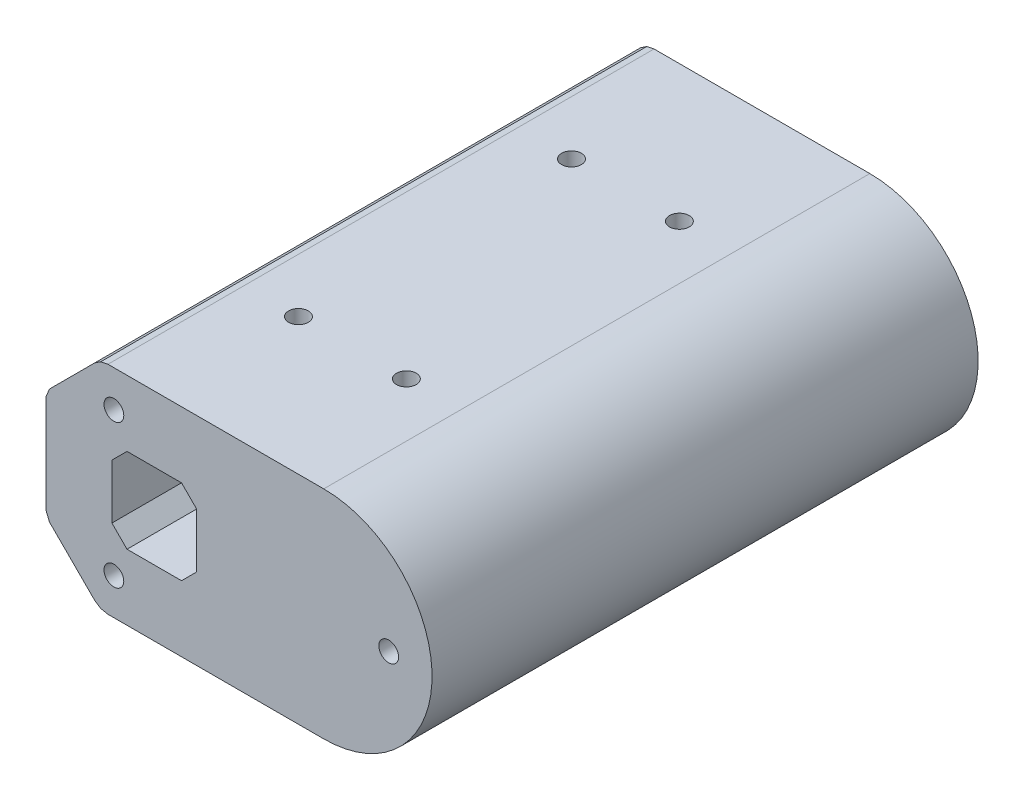
SolidWorks part; units mm, degrees
ref_plane "前视基准面" through (0, 0, 0) normal (0, 0, 1) x (1, 0, 0)
ref_plane "上视基准面" through (0, 0, 0) normal (0, 1, 0) x (1, 0, 0)
ref_plane "右视基准面" through (0, 0, 0) normal (1, 0, 0) x (0, 0, -1)
sketch "草图2" plane through (0, 0, -72.5002) normal (0, 0, 1) x (1, 0, 0)
  line L2 (-9.8402, -23) -> (-11.3737, -22.695)
  line L3 (-11.3737, -22.695) -> (-12.6737, -21.8263)
  line L4 (-12.6737, -21.8263) -> (-22.2579, -12.2421)
  line L5 (-22.2579, -12.2421) -> (-23, -10.4505)
  line L6 (-23, -10.4505) -> (-23, 10.4505)
  line L7 (-23, 10.4505) -> (-22.2579, 12.2421)
  line L8 (-22.2579, 12.2421) -> (-12.6737, 21.8263)
  line L9 (-12.6737, 21.8263) -> (-11.3737, 22.695)
  line L10 (-11.3737, 22.695) -> (-9.8402, 23)
  line L11 (-9.8402, 23) -> (36, 23)
  line L12 (-9.8402, -23) -> (36, -23)
  arc A3 (36, -23) -> (36, 23) centre (36, 0) ccw
extrude "凸台-拉伸1" add sketch "草图2" along normal up to surface (19 mm away)
sketch "草图4" plane through (0, 0, -53.5002) normal (0, 0, 1) x (1, 0, 0)
  line L0 (5.79, -9) -> (-5.79, -9)
  line L1 (-5.79, -9) -> (-9, -5.79)
  line L2 (-9, -5.79) -> (-9, 5.79)
  line L3 (-9, 5.79) -> (-5.79, 9)
  line L4 (-5.79, 9) -> (5.79, 9)
  line L5 (5.79, 9) -> (9, 5.79)
  line L6 (9, 5.79) -> (9, -5.79)
  line L7 (9, -5.79) -> (5.79, -9)
extrude "切除-拉伸1" cut sketch "草图4" against normal up to next
sketch "草图7" plane through (0, 0, -72.5002) normal (0, 0, -1) x (-1, 0, 0)
  line L0 (-36, 23) -> (9.8402, 23)
  line L1 (9.8402, 23) -> (11.3737, 22.695)
  line L2 (11.3737, 22.695) -> (12.6737, 21.8263)
  line L3 (12.6737, 21.8263) -> (22.2579, 12.2421)
  line L4 (22.2579, 12.2421) -> (22.6289, 11.3463)
  line L5 (22.2579, 12.2421) -> (23, 10.4505) construction
  line L6 (22.6289, 11.3463) -> (23, 10.4505)
  line L7 (23, 10.4505) -> (23, -10.4505)
  line L8 (23, -10.4505) -> (22.6289, -11.3463)
  line L9 (23, -10.4505) -> (22.2579, -12.2421) construction
  line L10 (22.6289, -11.3463) -> (22.2579, -12.2421)
  line L11 (22.2579, -12.2421) -> (12.6737, -21.8263)
  line L12 (12.6737, -21.8263) -> (11.3737, -22.695)
  line L13 (11.3737, -22.695) -> (9.8402, -23)
  line L14 (9.8402, -23) -> (-36, -23)
  line L15 (3.2525, 20) -> (8.5567, 20)
  line L17 (20, 9.0874) -> (20, -9.0874)
  line L18 (19.3547, -10.6453) -> (11.0206, -18.9794)
  line L19 (8.5567, -20) -> (-36, -20)
  line L20 (-36, 20) -> (3.2525, 20)
  line L21 (11.0206, 18.9794) -> (19.3547, 10.6453)
  arc A1 (-36, 23) -> (-36, -23) centre (-36, 0) ccw
  arc A2 (19.3547, 10.6453) -> (20, 9.0874) centre (17.7967, 9.0874) cw
  arc A3 (20, -9.0874) -> (19.3547, -10.6453) centre (17.7967, -9.0874) cw
  arc A4 (11.0206, -18.9794) -> (8.5567, -20) centre (8.5567, -16.5155) cw
  arc A5 (-36, -20) -> (-36, 20) centre (-36, 0) cw
  arc A6 (8.5567, 20) -> (11.0206, 18.9794) centre (8.5567, 16.5155) cw
extrude "凸台-拉伸2" add sketch "草图7" along normal up to surface (97 mm away)
sketch "草图8" plane through (0, 0, -53.5002) normal (0, 0, 1) x (1, 0, 0)
  circle A0 centre (49.8, 0) radius 2.1
  circle A1 centre (-8.58, -15.24) radius 2.1
  circle A2 centre (-8.58, 15.24) radius 2.1
  dimension "D1" = 4.2
  dimension "D2" = 4.2
  dimension "D3" = 4.2
extrude "切除-拉伸2" cut sketch "草图8" against normal up to next
sketch "草图9" plane through (0, -23, 0) normal (0, -1, 0) x (1, 0, 0)
  line L0 (36, -169.5002) -> (36, -53.5002) construction
  line L1 (36, -111.5002) -> (-9.8402, -111.5002) construction
  line L2 (-9.8402, -53.5002) -> (-9.8402, -169.5002) construction
  line L3 (-9.8402, -111.5002) -> (36, -53.5002) construction
  line L4 (36, -53.5002) -> (-9.8402, -53.5002) construction
  line L5 (-9.8402, -53.5002) -> (36, -111.5002) construction
  line L6 (13.0799, -82.5002) -> (36, -82.5002) construction
  line L7 (13.0799, -82.5002) -> (-9.8402, -82.5002) construction
  line L8 (13.0799, -140.5002) -> (36, -140.5002) construction
  line L9 (13.0799, -140.5002) -> (-9.8402, -140.5002) construction
hole_wizard "M5 螺纹孔1" positions "草图10" profile "草图11" tap size "M5" standard "GB"
sketch "草图10" plane through (0, -23, 0) normal (0, -1, 0) x (-1, 0, 0)
  line L0 (-13.0799, 82.5002) -> (9.8402, 82.5002) construction
  line L1 (-13.0799, 82.5002) -> (-36, 82.5002) construction
  line L2 (-13.0799, 140.5002) -> (-36, 140.5002) construction
  line L3 (-13.0799, 140.5002) -> (9.8402, 140.5002) construction
  point P0 (-1.6199, 82.5002)
  point P4 (-24.54, 82.5002)
  point P8 (-24.54, 140.5002)
  point P12 (-1.6199, 140.5002)
sketch "草图11" plane through (1.6199, -23, -82.5002) normal (1, 0, 0) x (0, 0, -1)
  line L0 (0, 0) -> (0, 3)
  line L1 (0, 3) -> (2.1, 3)
  line L2 (2.1, 3) -> (2.1, 0)
  line L5 (2.1, 0) -> (0, 0)
  line L11 (0, -6.35) -> (0, 107.95) construction
  dimension "通孔螺纹孔钻头直径" = 4.2
  dimension "通孔螺纹孔钻头深度" = 3
cosmetic thread "孔螺蚊线1"
cosmetic thread "孔螺蚊线2"
cosmetic thread "孔螺蚊线3"
cosmetic thread "孔螺蚊线4"
hole_wizard "M5 螺纹孔2" positions "草图12" profile "草图13" tap size "M5" standard "GB" end condition up to next
sketch "草图12" plane through (0, 23, 0) normal (0, 1, 0) x (1, 0, 0)
  line L0 (13.0799, 140.5002) -> (36, 140.5002) construction
  line L1 (13.0799, 140.5002) -> (-9.8402, 140.5002) construction
  line L2 (13.0799, 82.5002) -> (36, 82.5002) construction
  line L3 (13.0799, 82.5002) -> (-9.8402, 82.5002) construction
  point P0 (24.54, 140.5002)
  point P4 (1.6199, 140.5002)
  point P8 (24.54, 82.5002)
  point P12 (1.6199, 82.5002)
sketch "草图13" plane through (24.54, 23, -140.5002) normal (1, 0, 0) x (0, 0, 1)
  line L0 (0, 0) -> (0, 3)
  line L1 (0, 3) -> (2.1, 3)
  line L2 (2.1, 3) -> (2.1, 0)
  line L5 (2.1, 0) -> (0, 0)
  line L11 (0, -6.35) -> (0, 107.95) construction
  dimension "通孔螺纹孔钻头直径" = 4.2
  dimension "通孔螺纹孔钻头深度" = 3
cosmetic thread "孔螺蚊线5"
cosmetic thread "孔螺蚊线6"
cosmetic thread "孔螺蚊线7"
cosmetic thread "孔螺蚊线8"
